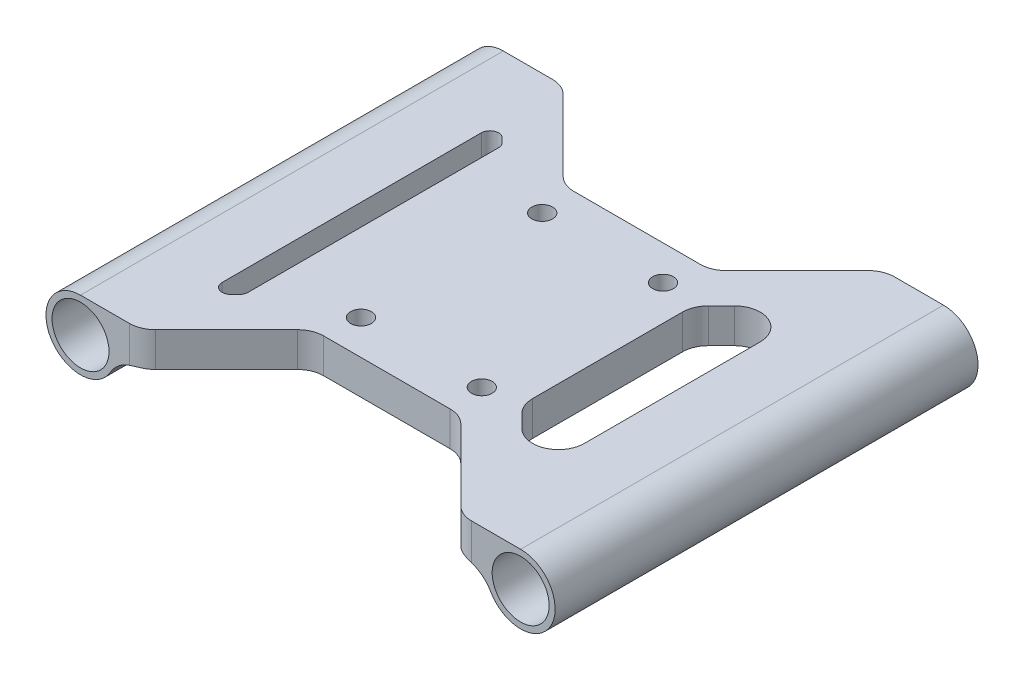
SolidWorks part; units mm, degrees
material "ABS"
ref_plane "Front Plane" through (0, 0, 0) normal (0, 0, 1) x (1, 0, 0)
ref_plane "Top Plane" through (0, 0, 0) normal (0, 1, 0) x (1, 0, 0)
ref_plane "Right Plane" through (0, 0, 0) normal (1, 0, 0) x (0, 0, -1)
sketch "Sketch1" plane through (0, 0, 0) normal (0, 0, 1) x (1, 0, 0)
  line L0 (-25.5, 4) -> (25.5, 4)
  line L1 (0, 4) -> (0, 0) construction
  line L2 (21.5, 0) -> (-21.5, 0)
  circle A0 centre (-25.5, 0) radius 4
  circle A1 centre (25.5, 0) radius 4
  dimension "D1" = 8
  dimension "D2" = 25.5
extrude "Boss-Extrude1" add sketch "Sketch1" along normal mid plane 49 contours A0 | L1 L0 A0 L2 | L0 L1 L2 A1 | A1
fillet "Fillet1" radius 4 2 edges at (21.5, 0, 0) (-21.5, 0, 0)
hole_wizard "M6 Clearance Hole1" positions "Sketch2" profile "Sketch3" hole size "M6" standard "ANSI Metric" end condition through all
sketch "Sketch2" plane through (0, 0, 24.5) normal (0, 0, 1) x (1, 0, 0)
  point P0 (-25.5, 0)
  point P3 (25.5, 0)
sketch "Sketch3" plane through (-25.5, 0, 24.5) normal (1, 0, 0) x (0, -1, 0)
  line L0 (0, 0) -> (0, 49)
  line L1 (0, 49) -> (3.3, 49)
  line L2 (3.3, 49) -> (3.3, 0)
  line L5 (3.3, 0) -> (0, 0)
  line L11 (0, -6.35) -> (0, 107.95) construction
  dimension "Thru Hole Dia." = 6.6
  dimension "Thru Hole Depth" = 49
hole_wizard "M2 Clearance Hole1" positions "Sketch4" profile "Sketch5" hole size "M2" standard "ANSI Metric" end condition through all
sketch "Sketch4" plane through (0, 4, 0) normal (0, 1, 0) x (1, 0, 0)
  point P0 (-7, 10.5)
  point P3 (7, 10.5)
  point P6 (7, -10.5)
  point P9 (-7, -10.5)
sketch "Sketch5" plane through (-7, 4, -10.5) normal (1, 0, 0) x (0, 0, 1)
  line L0 (0, 0) -> (0, 8)
  line L1 (0, 8) -> (1.2, 8)
  line L2 (1.2, 8) -> (1.2, 0)
  line L5 (1.2, 0) -> (0, 0)
  line L11 (0, -6.35) -> (0, 107.95) construction
  dimension "Thru Hole Dia." = 2.4
  dimension "Thru Hole Depth" = 8
sketch "Sketch6" plane through (0, 4, 0) normal (0, 1, 0) x (1, 0, 0)
  line L0 (-18.5718, 24.5) -> (-8.5718, 14.5)
  line L1 (-25.5, 24.5) -> (25.5, 24.5) construction
  line L2 (-8.5718, 14.5) -> (8.5718, 14.5)
  line L3 (0, 14.5) -> (0, 24.5)
  line L4 (0, 24.5) -> (-18.5718, 24.5)
  line L5 (-18.5718, -24.5) -> (-18.5718, 24.5) construction
  line L6 (18.5718, 24.5) -> (8.5718, 14.5)
  line L7 (0, 0) -> (-18.5718, 0) construction
  line L8 (-18.5718, -24.5) -> (-8.5718, -14.5)
  line L9 (18.5718, -24.5) -> (8.5718, -14.5)
  line L10 (-8.5718, -14.5) -> (8.5718, -14.5)
  line L11 (18.5718, 17.4289) -> (11.0718, 9.9289)
  line L12 (11.0718, 9.9289) -> (11.0718, -9.9289)
  line L13 (11.0718, 0) -> (18.5718, 0) construction
  line L14 (18.5718, -17.4289) -> (18.5718, 17.4289)
  line L15 (18.5718, -17.4289) -> (11.0718, -9.9289)
  line L16 (-18.5718, 17.4289) -> (-16.0718, 14.9289)
  line L17 (-16.0718, 14.9289) -> (-16.0718, -14.9289)
  line L18 (-18.5718, -0.0034) -> (-18.5718, 17.4289)
  line L19 (-18.5718, -17.4289) -> (-16.0718, -14.9289)
  line L20 (-18.5718, 0.0034) -> (-18.5718, -17.4289)
  point P33 (-16.0718, 0)
  line M15 (25.5, 24.5) -> (-25.5, 24.5)
  line M17 (-25.5, -24.5) -> (25.5, -24.5)
  dimension "D1" = 135
  dimension "D2" = 10
  dimension "D3" = 7.5
  dimension "D4" = 5
  dimension "D5" = 2.5
  dimension "D6" = 5
extrude "Cut-Extrude1" cut sketch "Sketch6" against normal through all and the other way through all contours L6 L3 L2 M15 | L2 L3 L0 M15 | L15 L14 L11 L12 | L10 L8 L9 M17 | L18 L20 L19 L17 L16
fillet "Fillet3" radius 3 12 edges at (18.5718, 2, -17.4289) (18.5718, 2, 17.4289) (11.0718, 2, 9.9289) (11.0718, 2, -9.9289) (18.5718, 2, -24.5) (8.5718, 2, -14.5) (-8.5718, 2, -14.5) (-18.5718, 2, -24.5) (-8.5718, 2, 14.5) (8.5718, 2, 14.5) (18.5718, 2, 24.5) (-18.5718, 2, 24.5)
fillet "Fillet4" radius 1 4 edges at (-18.5718, 2, -17.4289) (-16.0718, 2, -14.9289) (-18.5718, 2, 17.4289) (-16.0718, 2, 14.9289)
